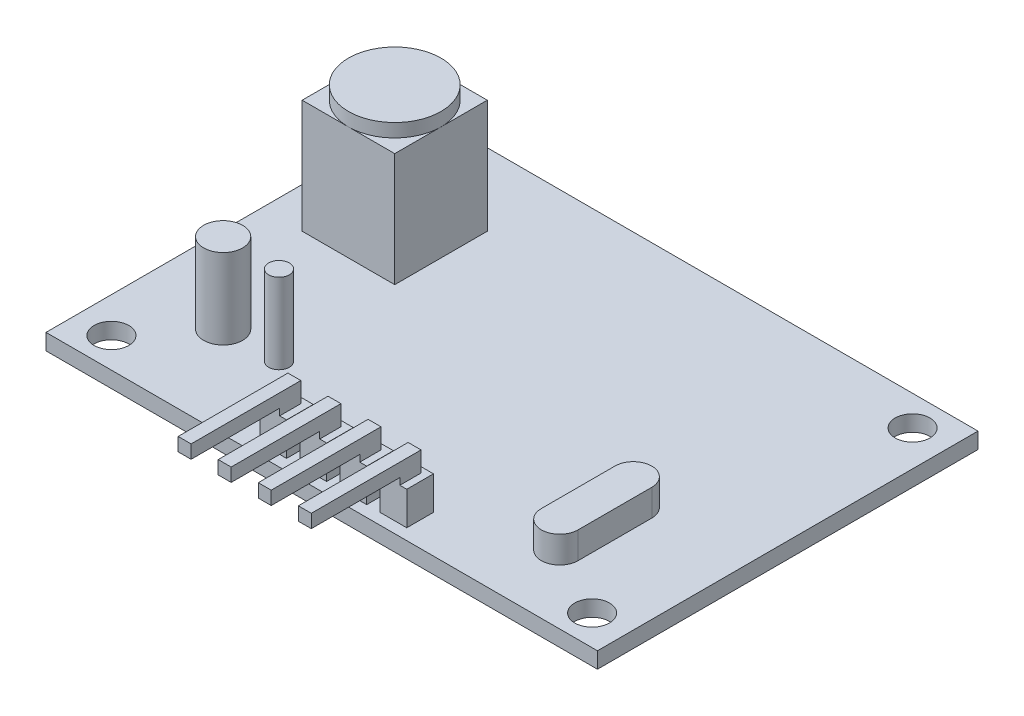
SolidWorks part; units mm, degrees
ref_plane "前视基准面" through (0, 0, 0) normal (0, 0, 1) x (1, 0, 0)
ref_plane "上视基准面" through (0, 0, 0) normal (0, 1, 0) x (1, 0, 0)
ref_plane "右视基准面" through (0, 0, 0) normal (1, 0, 0) x (0, 0, -1)
sketch "草图1" plane through (0, 0, 0) normal (0, 1, 0) x (1, 0, 0)
  line L1 (20.65, -14.25) -> (-20.65, -14.25)
  line L2 (20.65, -14.25) -> (20.65, 14.25)
  line L3 (20.65, 14.25) -> (-20.65, 14.25)
  line L4 (-20.65, -14.25) -> (-20.65, 14.25)
  line L5 (20.65, -14.25) -> (-20.65, 14.25) construction
  line L6 (20.65, 14.25) -> (-20.65, -14.25) construction
  point P0 (0, 0)
  dimension "D1" = 41.3
  dimension "D2" = 28.5
extrude "凸台-拉伸1" add sketch "草图1" along normal blind 1.2
sketch "草图2" plane through (0, 1.2, 0) normal (0, 1, 0) x (1, 0, 0)
  circle A0 centre (-14.1512, 5.3685) radius 3.4662
extrude "凸台-拉伸2" add sketch "草图2" along normal blind 9.5
sketch "草图3" plane through (0, 0, 0) normal (0, -1, 0) x (1, 0, 0)
  line L1 (-3.7, 2.9) -> (3.7, 2.9)
  line L2 (-3.7, 2.9) -> (-3.7, -2.9)
  line L3 (-3.7, -2.9) -> (3.7, -2.9)
  line L4 (3.7, 2.9) -> (3.7, -2.9)
  line L5 (-3.7, 2.9) -> (3.7, -2.9) construction
  line L6 (-3.7, -2.9) -> (3.7, 2.9) construction
  point P0 (0, 0)
  dimension "D1" = 7.4
  dimension "D2" = 5.8
extrude "凸台-拉伸3" add sketch "草图3" along normal blind 7.1
hole_wizard "M2 间隙孔1" positions "草图4" profile "草图5" hole size "M2" standard "GB" end condition up to next
sketch "草图4" plane through (0, 0, 0) normal (0, -1, 0) x (-1, 0, 0)
  line L0 (0, 0) -> (0, 5.6733) construction
  line L2 (0, 0) -> (9.453, 0) construction
  point P0 (18, -12)
  point P2 (-18, -12)
  point P4 (-18, 12)
  point P6 (18, 12)
  dimension "D1" = 36
  dimension "D2" = 24
sketch "草图5" plane through (-18, 0, 12) normal (1, 0, 0) x (0, 0, -1)
  line L0 (0, 0) -> (0, 1.2)
  line L1 (0, 1.2) -> (1.3, 1.2)
  line L2 (1.3, 1.2) -> (1.3, 0)
  line L5 (1.3, 0) -> (0, 0)
  line L11 (0, -6.35) -> (0, 107.95) construction
  dimension "通孔孔直径" = 2.6
  dimension "通孔孔深度" = 1.2
sketch "草图6" plane through (0, 1.2, 0) normal (0, 1, 0) x (1, 0, 0)
  line L0 (20.65, 14.25) -> (-20.65, 14.25) construction
  line L1 (-4.9515, -11.4151) -> (-3.9831, -11.4151)
  line L2 (-4.9515, -11.4151) -> (-4.9515, -20.05)
  line L3 (-4.9515, -20.05) -> (-3.9831, -20.05)
  line L4 (-3.9831, -11.4151) -> (-3.9831, -20.05)
  line L5 (-4.9515, -11.4151) -> (-3.9831, -20.05) construction
  line L6 (-4.9515, -20.05) -> (-3.9831, -11.4151) construction
  line L7 (-1.9515, -11.4151) -> (-1.9515, -20.05)
  line L8 (-0.9831, -11.4151) -> (-0.9831, -20.05)
  line L9 (-1.9515, -11.4151) -> (-0.9831, -11.4151)
  line L10 (-1.9515, -20.05) -> (-0.9831, -20.05)
  line L11 (1.0485, -11.4151) -> (1.0485, -20.05)
  line L12 (2.0169, -11.4151) -> (2.0169, -20.05)
  line L13 (1.0485, -11.4151) -> (2.0169, -11.4151)
  line L14 (1.0485, -20.05) -> (2.0169, -20.05)
  line L15 (4.0485, -11.4151) -> (4.0485, -20.05)
  line L16 (5.0169, -11.4151) -> (5.0169, -20.05)
  line L17 (4.0485, -11.4151) -> (5.0169, -11.4151)
  line L18 (4.0485, -20.05) -> (5.0169, -20.05)
  point P0 (-4.4673, -15.7326)
  dimension "D1" = 34.3
  dimension "D2" = 4
extrude "凸台-拉伸4" add sketch "草图6" along normal blind 4
sketch "草图7" plane through (5.0169, 0, 0) normal (1, 0, 0) x (0, 0, -1)
  line L0 (-20.05, 5.2) -> (-11.4151, 5.2) construction
  line L1 (-20.05, 1.2) -> (-13.4151, 1.2)
  line L2 (-20.05, 1.2) -> (-20.05, 4.2)
  line L3 (-20.05, 4.2) -> (-13.4151, 4.2)
  line L4 (-13.4151, 1.2) -> (-13.4151, 4.2)
  line L5 (-11.4151, 5.2) -> (-11.4151, 1.2) construction
  point P7 (-13.4151, 2.7)
  dimension "D1" = 1
  dimension "D2" = 2
extrude "切除-拉伸1" cut sketch "草图7" against normal through all
sketch "草图8" plane through (0, 10.7, 0) normal (0, 1, 0) x (1, 0, 0)
  line L1 (-10.6851, 1.9023) -> (-17.6174, 1.9023)
  line L2 (-10.6851, 1.9023) -> (-10.6851, 8.8347)
  line L3 (-10.6851, 8.8347) -> (-17.6174, 8.8347)
  line L4 (-17.6174, 1.9023) -> (-17.6174, 8.8347)
  line L5 (-10.6851, 1.9023) -> (-17.6174, 8.8347) construction
  line L6 (-10.6851, 8.8347) -> (-17.6174, 1.9023) construction
  circle A0 centre (-14.1512, 5.3685) radius 3.4662 construction
  point P0 (-14.1512, 5.3685)
extrude "凸台-拉伸5" add sketch "草图8" against normal up to next from offset 1
sketch "草图9" plane through (0, 1.2, 0) normal (0, 1, 0) x (1, 0, 0)
  circle A0 centre (-14.2296, -7.4052) radius 1.4639
  circle A1 centre (-10.0444, -7.4052) radius 0.7707
extrude "凸台-拉伸6" add sketch "草图9" along normal blind 6
sketch "草图10" plane through (0, 1.2, 0) normal (0, 1, 0) x (1, 0, 0)
  line L0 (12.7033, -3.6139) -> (12.7033, -9.1285) construction
  line L1 (14.0819, -3.6139) -> (14.0819, -9.1285)
  line L2 (11.3246, -3.6139) -> (11.3246, -9.1285)
  arc A0 (14.0819, -3.6139) -> (11.3246, -3.6139) centre (12.7033, -3.6139) ccw
  arc A1 (11.3246, -9.1285) -> (14.0819, -9.1285) centre (12.7033, -9.1285) ccw
  point P2 (12.7033, -6.3712)
extrude "凸台-拉伸7" add sketch "草图10" along normal blind 2
sketch "草图11" plane through (0, 5.2, 0) normal (0, 1, 0) x (1, 0, 0)
  line L0 (-4.9515, -13.4151) -> (-3.9831, -13.4151) construction
  line L1 (-3.4673, -13.4151) -> (-5.4673, -13.4151)
  line L2 (-3.4673, -13.4151) -> (-3.4673, -11.4151)
  line L3 (-3.4673, -11.4151) -> (-5.4673, -11.4151)
  line L4 (-5.4673, -13.4151) -> (-5.4673, -11.4151)
  line L5 (-3.4673, -13.4151) -> (-5.4673, -11.4151) construction
  line L6 (-3.4673, -11.4151) -> (-5.4673, -13.4151) construction
  line L7 (-3.9831, -11.4151) -> (-4.9515, -11.4151) construction
  line L8 (-4.9515, -20.05) -> (-3.9831, -20.05) construction
  line L9 (-4.4673, -12.4151) -> (4.5327, -12.4151) construction
  line L10 (4.5327, -11.4151) -> (4.5327, -13.4151) construction
  line L11 (5.0169, -11.4151) -> (4.0485, -11.4151) construction
  line L12 (4.0485, -13.4151) -> (5.0169, -13.4151) construction
  line L13 (-1.4673, -11.4151) -> (-1.4673, -13.4151) construction
  line L14 (-0.9831, -11.4151) -> (-1.9515, -11.4151) construction
  line L15 (-1.9515, -13.4151) -> (-0.9831, -13.4151) construction
  line L16 (1.5327, -12.4151) -> (1.5327, -13.4151) construction
  line L18 (1.0485, -13.4151) -> (2.0169, -13.4151) construction
  line L20 (-0.4673, -13.4151) -> (-2.4673, -13.4151)
  line L21 (-0.4673, -13.4151) -> (-0.4673, -11.4151)
  line L22 (-0.4673, -11.4151) -> (-2.4673, -11.4151)
  line L23 (-2.4673, -13.4151) -> (-2.4673, -11.4151)
  line L24 (-0.4673, -13.4151) -> (-2.4673, -11.4151) construction
  line L25 (-0.4673, -11.4151) -> (-2.4673, -13.4151) construction
  line L26 (5.5327, -13.4151) -> (3.5327, -13.4151)
  line L27 (5.5327, -13.4151) -> (5.5327, -11.4151)
  line L28 (5.5327, -11.4151) -> (3.5327, -11.4151)
  line L29 (3.5327, -13.4151) -> (3.5327, -11.4151)
  line L30 (5.5327, -13.4151) -> (3.5327, -11.4151) construction
  line L31 (5.5327, -11.4151) -> (3.5327, -13.4151) construction
  line L32 (2.5327, -13.4151) -> (0.5327, -13.4151)
  line L33 (2.5327, -13.4151) -> (2.5327, -11.4151)
  line L34 (2.5327, -11.4151) -> (0.5327, -11.4151)
  line L35 (0.5327, -13.4151) -> (0.5327, -11.4151)
  line L36 (2.5327, -13.4151) -> (0.5327, -11.4151) construction
  line L37 (2.5327, -11.4151) -> (0.5327, -13.4151) construction
  point P0 (-4.4673, -12.4151)
  point P11 (-4.4673, -11.4151)
  point P19 (-4.4673, -20.05)
  point P35 (-1.4673, -12.4151)
extrude "凸台-拉伸8" add sketch "草图11" against normal up to surface (2.5 mm away) from offset 1.5 up to face at (-10.0444, 1.2, 8.1759) offset against normal yes
sketch "草图12" plane through (0, 5.2, 0) normal (0, 1, 0) x (1, 0, 0)
  line L0 (5.0169, -20.05) -> (5.0169, -11.4151) construction
  line L1 (-4.9515, -11.4151) -> (5.0169, -11.4151)
  line L2 (-4.9515, -11.4151) -> (-4.9515, -11.8285)
  line L3 (-4.9515, -11.8285) -> (5.0169, -11.8285)
  line L4 (5.0169, -11.4151) -> (5.0169, -11.8285)
extrude "切除-拉伸3" cut sketch "草图12" against normal up to surface (1.5 mm away) up to face at (-3.7252, 3.7, 12.4151)
